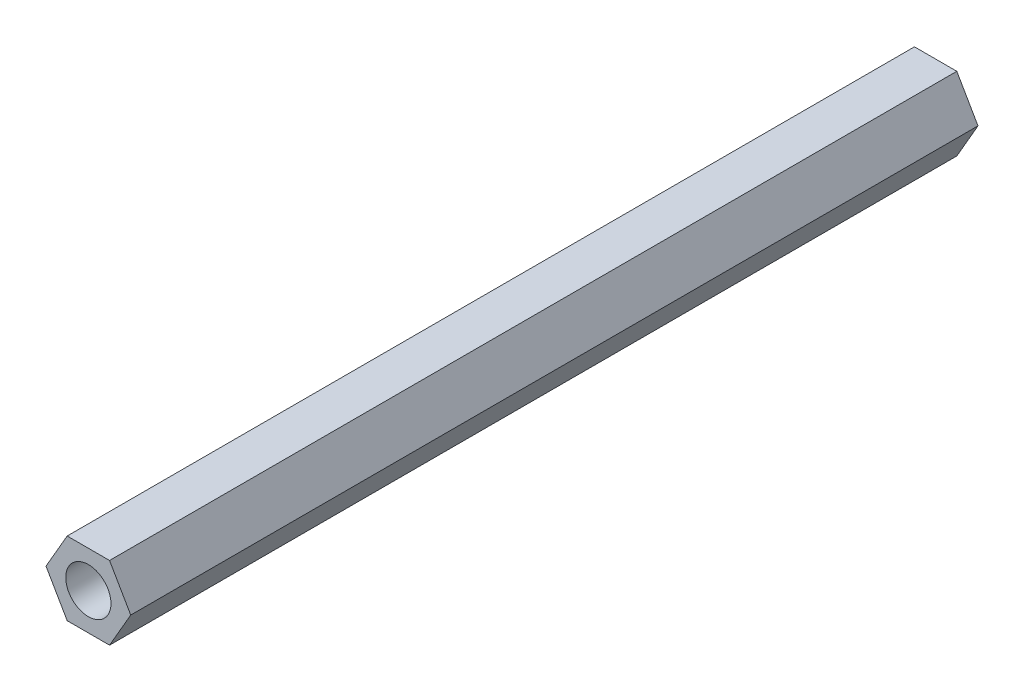
SolidWorks part; units mm, degrees
ref_plane "前视基准面" through (0, 0, 0) normal (0, 0, 1) x (1, 0, 0)
ref_plane "上视基准面" through (0, 0, 0) normal (0, 1, 0) x (1, 0, 0)
ref_plane "右视基准面" through (0, 0, 0) normal (1, 0, 0) x (0, 0, -1)
other "Configuration Table"
sketch "草图1" plane through (0, 0, 0) normal (0, 0, 1) x (1, 0, 0)
  line L1 (3, 0) -> (1.5, 2.5981)
  line L2 (1.5, 2.5981) -> (-1.5, 2.5981)
  line L3 (-1.5, 2.5981) -> (-3, 0)
  line L4 (-3, 0) -> (-1.5, -2.5981)
  line L5 (-1.5, -2.5981) -> (1.5, -2.5981)
  line L6 (1.5, -2.5981) -> (3, 0)
  circle A0 centre (0, 0) radius 1.6
  circle A1 centre (0, 0) radius 2.5981 construction
  dimension "D1" = 3.2
  dimension "D2" = 6
extrude "凸台-拉伸1" add sketch "草图1" along normal blind 60
